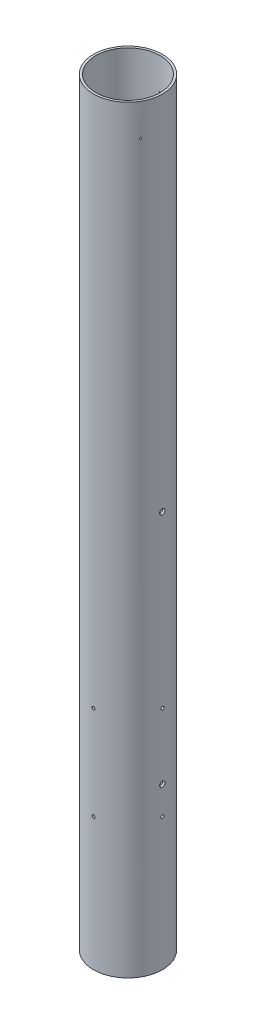
SolidWorks part; units mm, degrees
material "S1D_75 Degrees Custom Wound Fiberglass"
ref_plane "Front Plane" through (0, 0, 0) normal (0, 0, 1) x (1, 0, 0)
ref_plane "Top Plane" through (0, 0, 0) normal (0, 1, 0) x (1, 0, 0)
ref_plane "Right Plane" through (0, 0, 0) normal (1, 0, 0) x (0, 0, -1)
ref_axis "Axis1" through (0, -55, 0) along (0, 1, 0)
sketch "Sketch1" plane through (0, 0, 0) normal (0, 1, 0) x (1, 0, 0)
  circle A0 centre (0, 0) radius 38.1508
  circle A1 centre (0, 0) radius 40.8178
  dimension "D1" = 76.3016
  dimension "D2" = 2.667
extrude "Boss-Extrude1" add sketch "Sketch1" along normal blind 898.525
ref_plane "Top Surface" through (0, 898.525, 0) normal (0, 1, 0) x (1, 0, 0)
ref_plane "Fin Root Cord Plane" through (28.8625, 0, -28.8625) normal (0.7071, 0, -0.7071) x (0, -1, 0)
ref_plane "Motor Casing Centering Ring Plane" through (0, 0, 40.8178) normal (0, 0, 1) x (1, 0, 0)
ref_plane "Railguide Hole Plane" through (40.8178, 0, 0) normal (1, 0, 0) x (0, 0, -1)
sketch "Sketch2" plane through (40.8178, 0, 0) normal (1, 0, 0) x (0, 0, -1)
  line L0 (0, 898.525) -> (0, 0) construction
  circle A0 centre (0, 190.5) radius 3.175
  circle A1 centre (0, 469.9) radius 3.175
  dimension "D3" = 6.35
  dimension "D4" = 6.35
  dimension "D1" = 190.5
  dimension "D2" = 469.9
extrude "Railguide Hole Cut" cut sketch "Sketch2" against normal up to next
sketch "Sketch3" plane through (0, 0, 40.8178) normal (0, 0, 1) x (1, 0, 0)
  line L0 (0, -55) -> (0, 55) construction
  circle A0 centre (0, 157.1625) radius 1.778
  circle A1 centre (0, 268.2875) radius 1.778
  point P4 (0, 0)
  point P6 (0, 23.2043)
  point P9 (0, 0)
  point P10 (0, 0)
  point P11 (-269.9174, 8.6312)
  dimension "D3" = 3.556
  dimension "D4" = 3.556
  dimension "D1" = 157.1625
  dimension "D2" = 268.2875
extrude "Motor Casing Centering Ring Cut" cut sketch "Sketch3" against normal up to next
pattern_circular "CirPattern1" count 4 over 360 about axis through (0, -55, 0) along (0, 1, 0) of "Motor Casing Centering Ring Cut"
ref_plane "Shear Pin Plane" through (35.3493, 0, 20.4089) normal (0.866, 0, 0.5) x (0, -1, 0)
sketch "Sketch4" plane through (35.3493, 0, 20.4089) normal (0.866, 0, 0.5) x (0, -1, 0)
  line L0 (-898.525, 40.8178) -> (-898.525, -40.8178) construction
  circle A0 centre (-860.425, 0) radius 0.9906
  dimension "D2" = 1.9812
  dimension "D1" = 38.1
extrude "Shear Pin Cut" cut sketch "Sketch4" against normal up to next
pattern_circular "CirPattern2" count 3 over 360 about axis through (0, -55, 0) along (0, 1, 0) of "Shear Pin Cut"
ref_plane "Fin Midplane Work Plane 1" through (28.8625, 0, 28.8625) normal (0.7071, 0, 0.7071) x (0.7071, 0, -0.7071)
ref_plane "Fin Midplane Work Plane 2" through (-28.8625, 0, -28.8625) normal (-0.7071, 0, -0.7071) x (-0.7071, 0, 0.7071)
ref_plane "Fin Midplane" through (0, 0, 0) normal (-0.7071, 0, -0.7071) x (-0.7071, 0, 0.7071)
equation "\"D2@Sketch2\"=\"D1@Sketch2\"+11"
